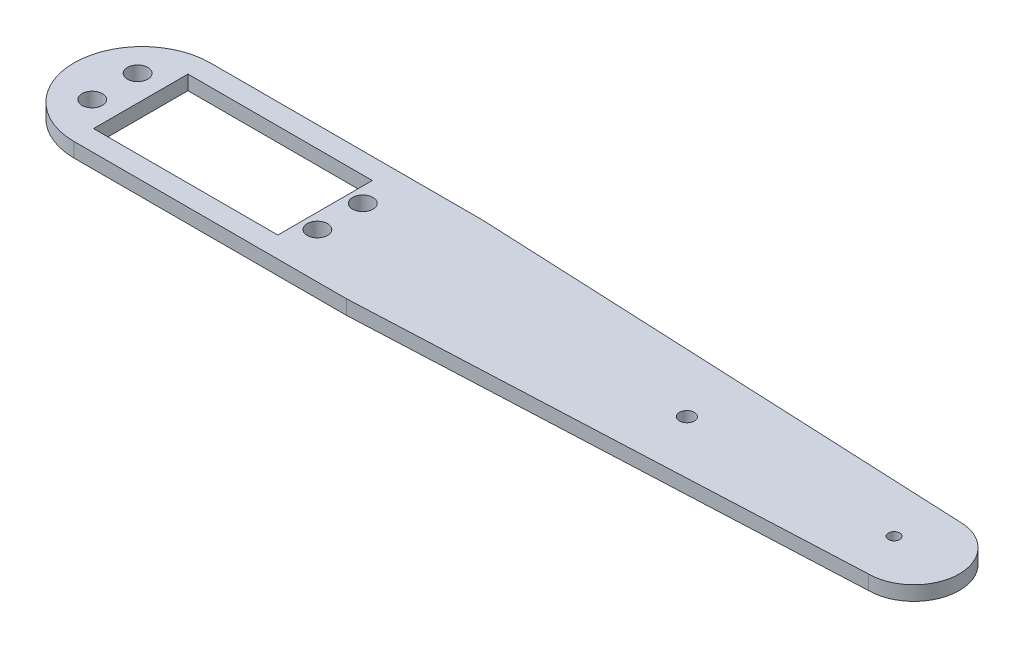
SolidWorks part; units mm, degrees
ref_plane "Front Plane" through (0, 0, 0) normal (0, 0, 1) x (1, 0, 0)
ref_plane "Top Plane" through (0, 0, 0) normal (0, 1, 0) x (1, 0, 0)
ref_plane "Right Plane" through (0, 0, 0) normal (1, 0, 0) x (0, 0, -1)
sketch "Sketch1" plane through (0, 0, 0) normal (0, 1, 0) x (1, 0, 0)
  line L0 (-162.3874, 17.2447) -> (-102.3874, 17.2447)
  line L1 (-102.3874, 17.2447) -> (7.6126, 12.2447)
  line L2 (-162.3874, -12.7553) -> (-102.3874, -12.7553)
  line L3 (-102.3874, -12.7553) -> (7.6126, -7.7553)
  line L4 (-168.3874, 19.311) -> (-168.3874, -13.0468) construction
  line L6 (-162.6926, -8.1553) -> (-122.0926, -8.1553)
  line L7 (-162.6926, -8.1553) -> (-162.6926, 12.6447)
  line L8 (-162.6926, 12.6447) -> (-122.0926, 12.6447)
  line L9 (-122.0926, -8.1553) -> (-122.0926, 12.6447)
  arc A0 (-162.3874, 17.2447) -> (-162.3874, -12.7553) centre (-162.3874, 2.2447) ccw
  arc A1 (7.6126, -7.7553) -> (7.6126, 12.2447) centre (7.6126, 2.2447) ccw
  circle A3 centre (-168.3874, 7.2447) radius 2.25
  circle A4 centre (-168.3874, -2.7553) radius 2.25
  circle A5 centre (-118.7874, 7.2447) radius 2.25
  circle A6 centre (-118.7874, -2.7553) radius 2.25
  circle A9 centre (-42.3874, 2.2447) radius 1.65
  circle A10 centre (3.2376, 2.2463) radius 1.2528
  dimension "D6" = 4.5
  dimension "D18" = 3.3
  dimension "D2" = 30
  dimension "D3" = 20
  dimension "D4" = 5
  dimension "D5" = 5
  dimension "D7" = 49.6
  dimension "D8" = 60
  dimension "D9" = 170
  dimension "D10" = 6
  dimension "D11" = 0
  dimension "D12" = 20.8
  dimension "D13" = 40.6
  dimension "D19" = 0.3053
  dimension "D14" = 10.19
  dimension "D15" = 0
  dimension "D16" = 50
extrude "Boss-Extrude1" add sketch "Sketch1" along normal blind 3.175
equation "\"D5@Sketch1\"=\"D4@Sketch1\""
